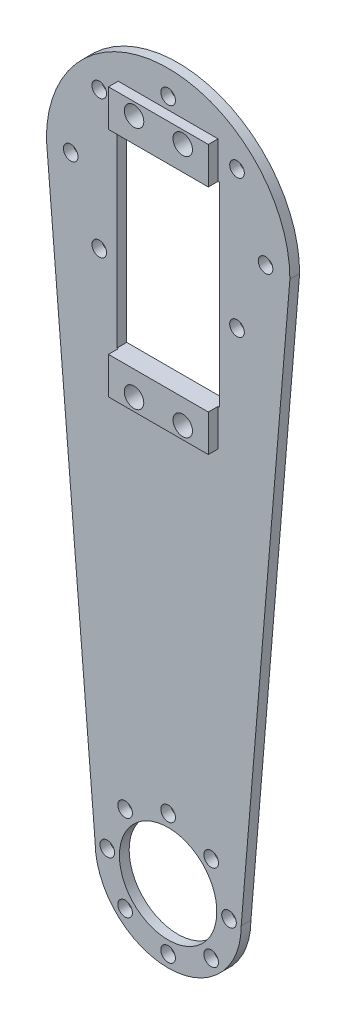
SolidWorks part; units mm, degrees
ref_plane "前视基准面" through (0, 0, 0) normal (0, 0, 1) x (1, 0, 0)
ref_plane "上视基准面" through (0, 0, 0) normal (0, 1, 0) x (1, 0, 0)
ref_plane "右视基准面" through (0, 0, 0) normal (1, 0, 0) x (0, 0, -1)
other "Configuration Table"
sketch "草图1" plane through (0, 0, 0) normal (0, 0, 1) x (1, 0, 0)
  line L0 (-1000, 0) -> (49000, 0) construction
  line L1 (-10.25, -20) -> (10.25, -20)
  line L2 (-10.25, -20) -> (-10.25, 20)
  line L3 (-10.25, 20) -> (10.25, 20)
  line L4 (10.25, -20) -> (10.25, 20)
  line L5 (-10.25, -20) -> (10.25, 20) construction
  line L6 (-10.25, 20) -> (10.25, -20) construction
  line L7 (-5, 15) -> (5, 15)
  line L8 (-5, 15) -> (-5, 25)
  line L9 (-5, 25) -> (5, 25)
  line L10 (5, 15) -> (5, 25)
  line L11 (-5, 15) -> (5, 25) construction
  line L12 (-5, 25) -> (5, 15) construction
  line L14 (-10.25, -35.1417) -> (10.25, -35.1417)
  line L15 (-10.25, -35.1417) -> (-10.25, 35.1417)
  line L16 (-10.25, 35.1417) -> (10.25, 35.1417)
  line L17 (10.25, -35.1417) -> (10.25, 35.1417)
  line L18 (-10.25, -35.1417) -> (10.25, 35.1417) construction
  line L19 (-10.25, 35.1417) -> (10.25, -35.1417) construction
  circle A0 centre (-5, 25) radius 2
  circle A1 centre (5, 25) radius 2
  circle A2 centre (5, -25) radius 2
  circle A3 centre (-5, -25) radius 2
  point P0 (0, 0)
  point P6 (0, 20)
  point P19 (0, 0)
  dimension "D5" = 4
  dimension "D6" = 4
  dimension "D1" = 20.5
  dimension "D2" = 40
  dimension "D3" = 10
  dimension "D4" = 10
extrude "凸台-拉伸1" add sketch "草图1" along normal blind 29 contours A1 L10 L3 L17 L16 L15 L8 A0 L9 | L14 L17 L1 L15 A2 A3 | A1 L9 A0 L8 L3 L10
sketch "草图2" plane through (0, 0, 29) normal (0, 0, 1) x (1, 0, 0)
  line L1 (-10.25, 35.1417) -> (10.25, 35.1417)
  line L2 (-10.25, 35.1417) -> (-10.25, -35.1417)
  line L3 (-10.25, -35.1417) -> (10.25, -35.1417)
  line L4 (10.25, 35.1417) -> (10.25, -35.1417)
extrude "凸台-拉伸2" add sketch "草图2" along normal blind 3
sketch "草图3" plane through (0, 0, 0) normal (0, 0, -1) x (-1, 0, 0)
  line L0 (-10.25, -35.1417) -> (-10.25, -20) construction
  line L1 (-10.25, -27.5709) -> (10.25, -27.5709)
  line L2 (-10.25, -27.5709) -> (-10.25, 27.5709)
  line L3 (-10.25, 27.5709) -> (10.25, 27.5709)
  line L4 (10.25, -27.5709) -> (10.25, 27.5709)
  line L5 (10.25, 20) -> (10.25, 35.1417) construction
  line L7 (-10.25, -35.1417) -> (10.25, -35.1417)
  line L8 (-10.25, -35.1417) -> (-10.25, 35.1417)
  line L9 (-10.25, 35.1417) -> (10.25, 35.1417)
  line L10 (10.25, -35.1417) -> (10.25, 35.1417)
  line M2 (-10.25, -35.1417) -> (10.25, -35.1417)
  line M3 (10.25, -35.1417) -> (10.25, -20)
  line M5 (-10.25, -20) -> (-10.25, -35.1417)
extrude "切除-拉伸1" cut sketch "草图3" against normal through all contours L1 M5 M2 M3 | L3 L10 L9 L8
sketch "草图5" plane through (0, -27.5709, 0) normal (0, -1, 0) x (1, 0, 0)
  line L0 (0, 0) -> (0, 2.5)
  circle A0 centre (0, 2.5) radius 2.5
  dimension "D2" = 5
  dimension "D1" = 2.5
extrude "凸台-拉伸3" add sketch "草图5" along normal blind 10
sketch "草图8" plane through (0, 27.5709, 0) normal (0, 1, 0) x (1, 0, 0)
  line L0 (0, 0) -> (0, -2.5)
  line L1 (0, -2.5) -> (0, -16.5)
  line L2 (0, -16.5) -> (0, -26.5)
  circle A0 centre (0, -16.5) radius 1.6
  circle A1 centre (0, -26.5) radius 1.6
  dimension "D4" = 3.2
  dimension "D5" = 3.2
  dimension "D1" = 2.5
  dimension "D2" = 14
  dimension "D3" = 10
extrude "切除-拉伸2" cut sketch "草图8" against normal up to next
sketch "草图9" plane through (0, 0, 32) normal (0, 0, 1) x (1, 0, 0)
  line L1 (-10.25, 27.5709) -> (10.25, 27.5709)
  line L2 (-10.25, 27.5709) -> (-10.25, -27.5709)
  line L3 (-10.25, -27.5709) -> (10.25, -27.5709)
  line L4 (10.25, 27.5709) -> (10.25, -27.5709)
extrude "切除-拉伸3" cut sketch "草图9" against normal blind 30
sketch "草图11" plane through (0, -37.5709, 0) normal (0, -1, 0) x (1, 0, 0)
  circle A0 centre (0, 2.5) radius 2.5
extrude "切除-拉伸4" cut sketch "草图11" against normal blind 10
sketch "草图12" plane through (0, 0, 0) normal (0, 0, -1) x (-1, 0, 0)
  line L0 (0, 20) -> (0, 10)
  line L1 (10.25, 20) -> (-10.25, 20) construction
  line L2 (0, 10) -> (0, -110)
  line L3 (-25, 10) -> (-15, -110)
  line L4 (25, 10) -> (15, -110)
  line L6 (-10.25, 20) -> (10.25, 20)
  line L7 (-10.25, 20) -> (-10.25, -20)
  line L8 (-10.25, -20) -> (10.25, -20)
  line L9 (10.25, 20) -> (10.25, -20)
  line L10 (-10.5, -20) -> (10.5, -20)
  line L11 (-10.5, -20) -> (-10.5, 20)
  line L12 (-10.5, 20) -> (10.5, 20)
  line L13 (10.5, -20) -> (10.5, 20)
  line L14 (-10.5, -20) -> (10.5, 20) construction
  line L15 (-10.5, 20) -> (10.5, -20) construction
  circle A0 centre (0, 10) radius 25
  circle A1 centre (0, -110) radius 15
  circle A2 centre (-5, 25) radius 2
  circle A3 centre (5, 25) radius 2
  circle A4 centre (-5, -25) radius 2
  circle A5 centre (5, -25) radius 2
  point P29 (0, 0)
  dimension "D2" = 50
  dimension "D4" = 30
  dimension "D1" = 10
  dimension "D3" = 120
  dimension "D5" = 20.5
  dimension "D6" = 21
extrude "凸台-拉伸5" add sketch "草图12" along normal blind 2
sketch "草图13" plane through (0, 0, -2) normal (0, 0, -1) x (-1, 0, 0)
  circle A0 centre (0, -110) radius 10
  dimension "D1" = 20
extrude "切除-拉伸5" cut sketch "草图13" against normal blind 2
sketch "草图14" plane through (0, 0, -2) normal (0, 0, -1) x (-1, 0, 0)
  circle A0 centre (0, 10) radius 20
  circle A1 centre (-20, 10) radius 1.5
  circle A2 centre (-14.1421, 24.1421) radius 1.5
  circle A3 centre (0, 30) radius 1.5
  circle A4 centre (14.1421, 24.1421) radius 1.5
  circle A5 centre (20, 10) radius 1.5
  circle A6 centre (14.1421, -4.1421) radius 1.5
  circle A7 centre (0, -10) radius 1.5
  circle A8 centre (-14.1421, -4.1421) radius 1.5
  circle A9 centre (0, -110) radius 12.5
  circle A10 centre (0, -97.5) radius 1.5
  circle A11 centre (8.8388, -101.1612) radius 1.5
  circle A12 centre (12.5, -110) radius 1.5
  circle A13 centre (8.8388, -118.8388) radius 1.5
  circle A14 centre (0, -122.5) radius 1.5
  circle A15 centre (-8.8388, -118.8388) radius 1.5
  circle A16 centre (-12.5, -110) radius 1.5
  circle A17 centre (-8.8388, -101.1612) radius 1.5
  dimension "D1" = 40
  dimension "D2" = 3
  dimension "D4" = 25
  dimension "D5" = 3
  dimension "D3" = 8
  dimension "D6" = 8
extrude "切除-拉伸6" cut sketch "草图14" against normal through all contours A0 A8 | A0 A8 | A0 A1 | A0 A1 | A0 A2 | A0 A2 | A0 A3 | A0 A3 | A0 A4 | A0 A4 | A0 A5 | A0 A5 | A0 A6 | A0 A6 | A9 A13 | A9 A13 | A9 A12 | A9 A12 | A9 A11 | A9 A11 | A9 A10 | A9 A10 | A17 | A16 | A15 | A14
